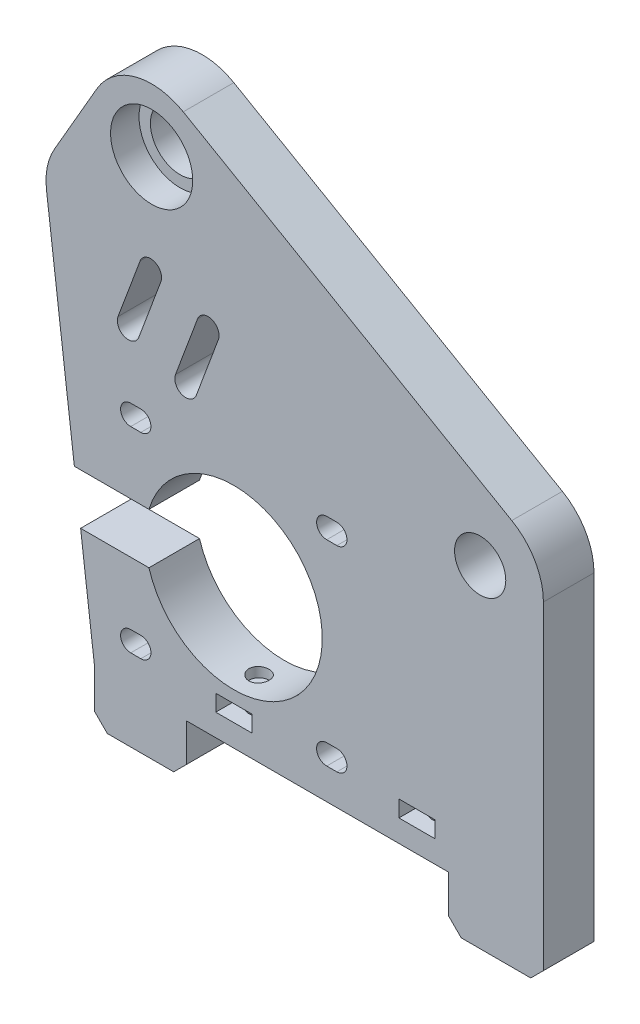
SolidWorks part; units mm, degrees
ref_plane "前视基准面" through (0, 0, 0) normal (0, 0, 1) x (1, 0, 0)
ref_plane "上视基准面" through (0, 0, 0) normal (0, 1, 0) x (1, 0, 0)
ref_plane "右视基准面" through (0, 0, 0) normal (1, 0, 0) x (0, 0, -1)
sketch "草图1" plane through (0, 0, 0) normal (0, 0, 1) x (1, 0, 0)
  line B0 (-25.2132, 4) -> (-29.6202, 39.6595)
  line B1 (-13.4164, 4) -> (-25.2132, 4)
  line B2 (-24.2245, -4) -> (-13.4164, -4)
  line B3 (-22, -22) -> (-24.2245, -4)
  line B4 (-7.5, -30) -> (-22, -30)
  line B5 (-7.5, -30) -> (-7.5, -22)
  line B6 (33.9711, -22) -> (-7.5, -22)
  line B7 (-14.7, 13.9) -> (-16.3, 13.9)
  line B8 (-16.3, 17.1) -> (-14.7, 17.1)
  line B9 (16.3, 13.9) -> (14.7, 13.9)
  line B10 (14.7, 17.1) -> (16.3, 17.1)
  line B11 (31.9711, -15.5) -> (25.9711, -15.5)
  line B12 (31.9711, -18.5) -> (31.9711, -15.5)
  line B13 (25.9711, -18.5) -> (31.9711, -18.5)
  line B14 (25.9711, -15.5) -> (25.9711, -18.5)
  line B15 (16.3, -17.1) -> (14.7, -17.1)
  line B16 (14.7, -13.9) -> (16.3, -13.9)
  line B17 (3, -15.5) -> (-3, -15.5)
  line B18 (3, -18.5) -> (3, -15.5)
  line B19 (-3, -18.5) -> (3, -18.5)
  line B20 (-3, -15.5) -> (-3, -18.5)
  line B21 (-14.7, -17.1) -> (-16.3, -17.1)
  line B22 (-16.3, -13.9) -> (-14.7, -13.9)
  line B23 (33.9711, -30) -> (33.9711, -22)
  line B24 (48.9711, -30) -> (33.9711, -30)
  line B25 (48.9711, 22.5) -> (48.9711, -30)
  line B26 (-22, -30) -> (-22, -22)
  line B27 (30.5711, -7) -> (27.3711, -7) construction
  line B28 (-17.025, -12.45) -> (-13.975, -12.45) construction
  line B29 (13.975, -12.45) -> (17.025, -12.45) construction
  line B30 (17.025, -18.55) -> (13.975, -18.55) construction
  line B31 (17.025, 12.45) -> (13.975, 12.45) construction
  line B32 (13.975, 18.55) -> (17.025, 18.55) construction
  line B33 (-13.975, 12.45) -> (-17.025, 12.45) construction
  line B34 (-17.025, 18.55) -> (-13.975, 18.55) construction
  line B35 (-13.975, -18.55) -> (-17.025, -18.55) construction
  line B36 (-1.6, -22) -> (-1.6, -18.5) construction
  line B37 (1.6, -18.5) -> (1.6, -22) construction
  line B38 (27.3711, -22) -> (27.3711, -18.5) construction
  line B39 (27.3711, -15.5) -> (27.3711, -7) construction
  line B40 (30.5711, -7) -> (30.5711, -15.5) construction
  line B41 (43.9711, 31.1603) -> (-7.9904, 61.1603)
  line B42 (-28.356, 45.886) -> (-21.6506, 57.5)
  circle B43 centre (-12.9904, 52.5) radius 6.5
  circle B44 centre (38.9711, 22.5) radius 4.05
  circle B45 centre (-12.9904, 52.5) radius 4.7
  arc B46 (-13.4164, -4) -> (-13.4164, 4) centre (0, 0) ccw
  arc B47 (-14.7, 13.9) -> (-14.7, 17.1) centre (-14.7, 15.5) ccw
  arc B48 (-16.3, 17.1) -> (-16.3, 13.9) centre (-16.3, 15.5) ccw
  arc B49 (16.3, 13.9) -> (16.3, 17.1) centre (16.3, 15.5) ccw
  arc B50 (14.7, 17.1) -> (14.7, 13.9) centre (14.7, 15.5) ccw
  arc B51 (16.3, -17.1) -> (16.3, -13.9) centre (16.3, -15.5) ccw
  arc B52 (14.7, -13.9) -> (14.7, -17.1) centre (14.7, -15.5) ccw
  arc B53 (-14.7, -17.1) -> (-14.7, -13.9) centre (-14.7, -15.5) ccw
  arc B54 (-16.3, -13.9) -> (-16.3, -17.1) centre (-16.3, -15.5) ccw
  arc B55 (17.025, -18.55) -> (17.025, -12.45) centre (17.025, -15.5) ccw construction
  arc B56 (17.025, 12.45) -> (17.025, 18.55) centre (17.025, 15.5) ccw construction
  arc B57 (13.975, 18.55) -> (13.975, 12.45) centre (13.975, 15.5) ccw construction
  arc B58 (13.975, -12.45) -> (13.975, -18.55) centre (13.975, -15.5) ccw construction
  arc B59 (-17.025, 18.55) -> (-17.025, 12.45) centre (-17.025, 15.5) ccw construction
  arc B60 (-17.025, -12.45) -> (-17.025, -18.55) centre (-17.025, -15.5) ccw construction
  arc B61 (-13.975, -18.55) -> (-13.975, -12.45) centre (-13.975, -15.5) ccw construction
  arc B62 (-13.975, 12.45) -> (-13.975, 18.55) centre (-13.975, 15.5) ccw construction
  arc B63 (-7.9904, 61.1603) -> (-21.6506, 57.5) centre (-12.9904, 52.5) ccw
  arc B64 (48.9711, 22.5) -> (43.9711, 31.1603) centre (38.9711, 22.5) ccw
  arc B65 (-28.356, 45.886) -> (-29.6202, 39.6595) centre (-19.6957, 40.886) ccw
sketch_block_instance "mainStructure3-1_0-1"
sketch_block "mainStructure3-1_0"
sketch "草图3" plane through (0, 0, 0) normal (0, 0, 1) x (1, 0, 0)
  line L0 (43.9711, 31.1603) -> (-7.9904, 61.1603) construction
  line L1 (-28.356, 45.886) -> (-21.6506, 57.5) construction
  line L2 (-25.2132, 4) -> (-29.6202, 39.6595) construction
  line L3 (-13.4164, 4) -> (-25.2132, 4) construction
  line L4 (-24.2245, -4) -> (-13.4164, -4) construction
  line L5 (-22, -22) -> (-24.2245, -4) construction
  line L6 (-22, -30) -> (-22, -22) construction
  line L7 (-7.5, -30) -> (-22, -30) construction
  line L8 (33.9711, -22) -> (-7.5, -22) construction
  line L9 (-7.5, -30) -> (-7.5, -22) construction
  line L10 (48.9711, -30) -> (33.9711, -30) construction
  line L11 (33.9711, -30) -> (33.9711, -22) construction
  line L12 (48.9711, 22.5) -> (48.9711, -30) construction
  line L13 (-16.3, 17.1) -> (-14.7, 17.1) construction
  line L14 (-14.7, 13.9) -> (-16.3, 13.9) construction
  line L15 (14.7, 17.1) -> (16.3, 17.1) construction
  line L16 (16.3, 13.9) -> (14.7, 13.9) construction
  line L17 (14.7, -13.9) -> (16.3, -13.9) construction
  line L18 (16.3, -17.1) -> (14.7, -17.1) construction
  line L19 (-16.3, -13.9) -> (-14.7, -13.9) construction
  line L20 (-14.7, -17.1) -> (-16.3, -17.1) construction
  line L21 (43.9711, 31.1603) -> (-7.9904, 61.1603)
  line L22 (-28.356, 45.886) -> (-21.6506, 57.5)
  line L23 (-25.2132, 4) -> (-29.6202, 39.6595)
  line L24 (-13.4164, 4) -> (-25.2132, 4)
  line L25 (-24.2245, -4) -> (-13.4164, -4)
  line L26 (-22, -22) -> (-24.2245, -4)
  line L27 (-22, -30) -> (-22, -22)
  line L28 (-7.5, -30) -> (-22, -30)
  line L29 (33.9711, -22) -> (-7.5, -22)
  line L30 (-7.5, -30) -> (-7.5, -22)
  line L31 (48.9711, -30) -> (33.9711, -30)
  line L32 (33.9711, -30) -> (33.9711, -22)
  line L33 (48.9711, 22.5) -> (48.9711, -30)
  line L34 (-16.3, 17.1) -> (-14.7, 17.1)
  line L35 (-14.7, 13.9) -> (-16.3, 13.9)
  line L36 (14.7, 17.1) -> (16.3, 17.1)
  line L37 (16.3, 13.9) -> (14.7, 13.9)
  line L38 (14.7, -13.9) -> (16.3, -13.9)
  line L39 (16.3, -17.1) -> (14.7, -17.1)
  line L40 (-16.3, -13.9) -> (-14.7, -13.9)
  line L41 (-14.7, -17.1) -> (-16.3, -17.1)
  line L42 (3, -15.5) -> (-3, -15.5) construction
  line L44 (-3, -18.5) -> (3, -18.5) construction
  line L46 (31.9711, -15.5) -> (25.9711, -15.5) construction
  line L49 (25.9711, -18.5) -> (31.9711, -18.5) construction
  line L50 (3.1, -15.5) -> (-3.1, -15.5)
  line L51 (-3.1, -15.5) -> (-3.1, -18.5)
  line L52 (-3.1, -18.5) -> (3.1, -18.5)
  line L53 (3.1, -15.5) -> (3.1, -18.5)
  line L54 (32.0711, -15.5) -> (25.8711, -15.5)
  line L55 (-3, -15.5) -> (-3, -18.5) construction
  line L56 (25.8711, -15.5) -> (25.8711, -18.5)
  line L57 (25.8711, -18.5) -> (32.0711, -18.5)
  line L58 (32.0711, -15.5) -> (32.0711, -18.5)
  line L59 (25.9711, -15.5) -> (25.9711, -18.5) construction
  arc A0 (-7.9904, 61.1603) -> (-21.6506, 57.5) centre (-12.9904, 52.5) ccw construction
  arc A1 (-28.356, 45.886) -> (-29.6202, 39.6595) centre (-19.6957, 40.886) ccw construction
  arc A2 (-13.4164, -4) -> (-13.4164, 4) centre (0, 0) ccw construction
  arc A3 (48.9711, 22.5) -> (43.9711, 31.1603) centre (38.9711, 22.5) ccw construction
  circle A4 centre (38.9711, 22.5) radius 4.05 construction
  circle A5 centre (-12.9904, 52.5) radius 4.7 construction
  arc A6 (-14.7, 13.9) -> (-14.7, 17.1) centre (-14.7, 15.5) ccw construction
  arc A7 (-16.3, 17.1) -> (-16.3, 13.9) centre (-16.3, 15.5) ccw construction
  arc A8 (14.7, 17.1) -> (14.7, 13.9) centre (14.7, 15.5) ccw construction
  arc A9 (16.3, 13.9) -> (16.3, 17.1) centre (16.3, 15.5) ccw construction
  arc A10 (16.3, -17.1) -> (16.3, -13.9) centre (16.3, -15.5) ccw construction
  arc A11 (14.7, -13.9) -> (14.7, -17.1) centre (14.7, -15.5) ccw construction
  arc A12 (-16.3, -13.9) -> (-16.3, -17.1) centre (-16.3, -15.5) ccw construction
  arc A13 (-14.7, -17.1) -> (-14.7, -13.9) centre (-14.7, -15.5) ccw construction
  arc A14 (-7.9904, 61.1603) -> (-21.6506, 57.5) centre (-12.9904, 52.5) ccw
  arc A15 (-28.356, 45.886) -> (-29.6202, 39.6595) centre (-19.6957, 40.886) ccw
  arc A16 (-13.4164, -4) -> (-13.4164, 4) centre (0, 0) ccw
  arc A17 (48.9711, 22.5) -> (43.9711, 31.1603) centre (38.9711, 22.5) ccw
  circle A18 centre (38.9711, 22.5) radius 4.05
  circle A19 centre (-12.9904, 52.5) radius 4.7
  arc A20 (-14.7, 13.9) -> (-14.7, 17.1) centre (-14.7, 15.5) ccw
  arc A21 (-16.3, 17.1) -> (-16.3, 13.9) centre (-16.3, 15.5) ccw
  arc A22 (14.7, 17.1) -> (14.7, 13.9) centre (14.7, 15.5) ccw
  arc A23 (16.3, 13.9) -> (16.3, 17.1) centre (16.3, 15.5) ccw
  arc A24 (16.3, -17.1) -> (16.3, -13.9) centre (16.3, -15.5) ccw
  arc A25 (14.7, -13.9) -> (14.7, -17.1) centre (14.7, -15.5) ccw
  arc A26 (-16.3, -13.9) -> (-16.3, -17.1) centre (-16.3, -15.5) ccw
  arc A27 (-14.7, -17.1) -> (-14.7, -13.9) centre (-14.7, -15.5) ccw
  dimension "D1" = 6.2
  dimension "D2" = 0.1
  dimension "D3" = 6.2
  dimension "D4" = 0.1
extrude "凸台-拉伸1" add sketch "草图3" along normal blind 8
sketch "草图4" plane through (0, 0, 8) normal (0, 0, -1) x (-1, 0, 0)
  circle A0 centre (12.9904, 52.5) radius 6.5 construction
  circle A1 centre (12.9904, 52.5) radius 6.5
extrude "切除-拉伸1" cut sketch "草图4" along normal blind 4.5
sketch "草图5" plane through (0, 0, 0) normal (0, 0, 1) x (1, 0, 0)
  line L0 (-17.025, 18.55) -> (-13.975, 18.55) construction
  line L1 (-13.975, 12.45) -> (-17.025, 12.45) construction
  line L2 (13.975, 18.55) -> (17.025, 18.55) construction
  line L3 (17.025, 12.45) -> (13.975, 12.45) construction
  line L4 (13.975, -12.45) -> (17.025, -12.45) construction
  line L5 (17.025, -18.55) -> (13.975, -18.55) construction
  line L6 (-17.025, -12.45) -> (-13.975, -12.45) construction
  line L7 (-13.975, -18.55) -> (-17.025, -18.55) construction
  line L8 (-17.025, 18.55) -> (-13.975, 18.55)
  line L9 (-13.975, 12.45) -> (-17.025, 12.45)
  line L10 (13.975, 18.55) -> (17.025, 18.55)
  line L11 (17.025, 12.45) -> (13.975, 12.45)
  line L12 (13.975, -12.45) -> (17.025, -12.45)
  line L13 (17.025, -18.55) -> (13.975, -18.55)
  line L14 (-17.025, -12.45) -> (-13.975, -12.45)
  line L15 (-13.975, -18.55) -> (-17.025, -18.55)
  arc A0 (-13.975, 12.45) -> (-13.975, 18.55) centre (-13.975, 15.5) ccw construction
  arc A1 (-17.025, 18.55) -> (-17.025, 12.45) centre (-17.025, 15.5) ccw construction
  arc A2 (17.025, 12.45) -> (17.025, 18.55) centre (17.025, 15.5) ccw construction
  arc A3 (13.975, 18.55) -> (13.975, 12.45) centre (13.975, 15.5) ccw construction
  arc A4 (17.025, -18.55) -> (17.025, -12.45) centre (17.025, -15.5) ccw construction
  arc A5 (13.975, -12.45) -> (13.975, -18.55) centre (13.975, -15.5) ccw construction
  arc A6 (-13.975, -18.55) -> (-13.975, -12.45) centre (-13.975, -15.5) ccw construction
  arc A7 (-17.025, -12.45) -> (-17.025, -18.55) centre (-17.025, -15.5) ccw construction
  arc A8 (-13.975, 12.45) -> (-13.975, 18.55) centre (-13.975, 15.5) ccw
  arc A9 (-17.025, 18.55) -> (-17.025, 12.45) centre (-17.025, 15.5) ccw
  arc A10 (17.025, 12.45) -> (17.025, 18.55) centre (17.025, 15.5) ccw
  arc A11 (13.975, 18.55) -> (13.975, 12.45) centre (13.975, 15.5) ccw
  arc A12 (17.025, -18.55) -> (17.025, -12.45) centre (17.025, -15.5) ccw
  arc A13 (13.975, -12.45) -> (13.975, -18.55) centre (13.975, -15.5) ccw
  arc A14 (-13.975, -18.55) -> (-13.975, -12.45) centre (-13.975, -15.5) ccw
  arc A15 (-17.025, -12.45) -> (-17.025, -18.55) centre (-17.025, -15.5) ccw
extrude "切除-拉伸2" cut sketch "草图5" along normal blind 3
sketch "草图6" plane through (0, -22, 0) normal (0, -1, 0) x (1, 0, 0)
  line L0 (-7.5, 8) -> (-7.5, 0) construction
  line L1 (33.9711, 8) -> (33.9711, 0) construction
  line L2 (-7.5, 8) -> (33.9711, 8) construction
  circle A0 centre (0, 4) radius 1.6
  circle A1 centre (28.9711, 4) radius 1.6
  dimension "D4" = 3.2
  dimension "D1" = 7.5
  dimension "D2" = 5
  dimension "D3" = 4
extrude "切除-拉伸3" cut sketch "草图6" against normal up to vertex (15 mm away)
sketch "草图7" plane through (0, 0, 8) normal (0, 0, 1) x (1, 0, 0)
  line B0 (-9.216, 24.5748) -> (-5.7204, 33.944)
  line B1 (-5.9368, 23.3514) -> (-2.4412, 32.7205)
  line B2 (-18.3041, 27.9656) -> (-14.8085, 37.3347)
  line B3 (-15.0249, 26.7421) -> (-11.5293, 36.1112)
  arc B4 (-9.216, 24.5748) -> (-5.9368, 23.3514) centre (-7.5764, 23.9631) ccw
  arc B5 (-18.3041, 27.9656) -> (-15.0249, 26.7421) centre (-16.6645, 27.3538) ccw
  arc B6 (-2.4412, 32.7205) -> (-5.7204, 33.944) centre (-4.0808, 33.3322) ccw
  arc B7 (-11.5293, 36.1112) -> (-14.8085, 37.3347) centre (-13.1689, 36.723) ccw
  circle B8 centre (38.9711, 22.5) radius 4.05
sketch_block_instance "块1-1"
sketch_block "块1"
extrude "切除-拉伸4" cut sketch "草图7" against normal through all
chamfer "倒角1" distance 2 angle 45 4 edges at (48.9711, -30, 4) (33.9711, -30, 4) (-7.5, -30, 4) (-22, -30, 4)
sketch "草图9" plane through (0, 0, 8) normal (0, 0, 1) x (1, 0, 0)
  line L1 (2.85, -15.9) -> (-2.85, -15.9)
  line L2 (2.85, -15.9) -> (2.85, -18.5)
  line L3 (2.85, -18.5) -> (3.1, -18.5)
  line L4 (-2.85, -15.9) -> (-2.85, -18.5)
  line L5 (-3, -18.5) -> (3, -18.5) construction
  line L6 (3, -18.5) -> (3, -15.5) construction
  line L7 (25.9711, -18.5) -> (31.9711, -18.5) construction
  line L8 (31.8211, -15.9) -> (26.1211, -15.9)
  line L9 (31.8211, -15.9) -> (31.8211, -18.5)
  line L10 (31.8211, -18.5) -> (32.0711, -18.5)
  line L11 (26.1211, -15.9) -> (26.1211, -18.5)
  line L12 (25.9711, -15.5) -> (25.9711, -18.5) construction
  line L19 (32.0711, -18.5) -> (32.0711, -15.5)
  line L20 (32.0711, -15.5) -> (25.8711, -15.5)
  line L21 (25.8711, -15.5) -> (25.8711, -18.5)
  line L22 (3.1, -18.5) -> (3.1, -15.5)
  line L23 (3.1, -15.5) -> (-3.1, -15.5)
  line L24 (-3.1, -15.5) -> (-3.1, -18.5)
  line L25 (-3.1, -18.5) -> (-2.85, -18.5)
  line L26 (25.8711, -18.5) -> (26.1211, -18.5)
  dimension "D1" = 2.6
  dimension "D2" = 0.15
  dimension "D3" = 5.7
  dimension "D4" = 2.6
  dimension "D5" = 5.7
  dimension "D6" = 0.15
extrude "凸台-拉伸2" add sketch "草图9" against normal up to vertex (8 mm away)
